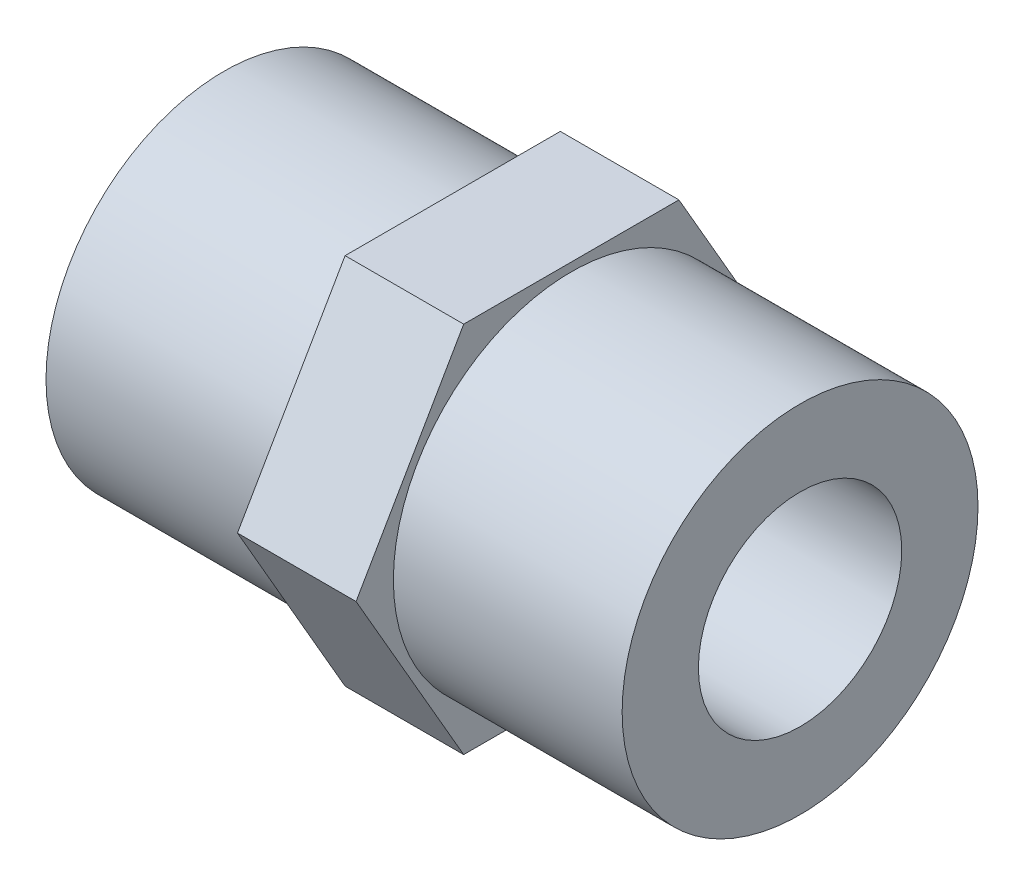
SolidWorks part; units mm, degrees
material "Acciaio inossidabile fuso"
ref_plane "Piano frontale" through (0, 0, 0) normal (0, 0, 1) x (1, 0, 0)
ref_plane "Piano superiore" through (0, 0, 0) normal (0, 1, 0) x (1, 0, 0)
ref_plane "Piano destro" through (0, 0, 0) normal (1, 0, 0) x (0, 0, -1)
sketch "Schizzo1" plane through (0, 0, 0) normal (0, 0, 1) x (1, 0, 0)
  line L0 (0, 0) -> (42.6268, 0) construction
  line L1 (0, 6) -> (0, 10.5)
  line L2 (0, 10.5) -> (13.5, 10.5)
  line L3 (13.5, 10.5) -> (13.5, 11)
  line L4 (13.5, 11) -> (20.5, 11)
  line L5 (20.5, 11) -> (20.5, 10.5)
  line L6 (20.5, 10.5) -> (34, 10.5)
  line L7 (34, 10.5) -> (34, 6)
  line L8 (34, 6) -> (0, 6)
  point P8 (0, 0)
  point P12 (0, 0)
  dimension "D1" = 13.5
  dimension "D2" = 12
  dimension "D3" = 21
  dimension "D4" = 34
  dimension "D5" = 22
revolve "Rivoluzione1" add sketch "Schizzo1" angle 360 about L0
sketch "Schizzo2" plane through (20.5, 0, 0) normal (1, 0, 0) x (0, 0, -1)
  line L0 (-12.7017, 0) -> (-6.3509, -11)
  line L1 (-6.3509, -11) -> (6.3509, -11)
  line L2 (6.3509, -11) -> (12.7017, 0)
  line L3 (12.7017, 0) -> (6.3509, 11)
  line L4 (6.3509, 11) -> (-6.3509, 11)
  line L5 (-6.3509, 11) -> (-12.7017, 0)
  circle A0 centre (0, 0) radius 11 construction
  circle A1 centre (0, 0) radius 11
  circle M7 centre (0, 0) radius 11
extrude "Estrusione-Estrusione1" add sketch "Schizzo2" against normal up to surface (7 mm away) contours L5 L0 M7 | L4 L5 M7 | L3 L4 M7 | L0 L1 M7 | L1 L2 M7 | L2 L3 M7 up to face at (13.5, 0, 10.5)
